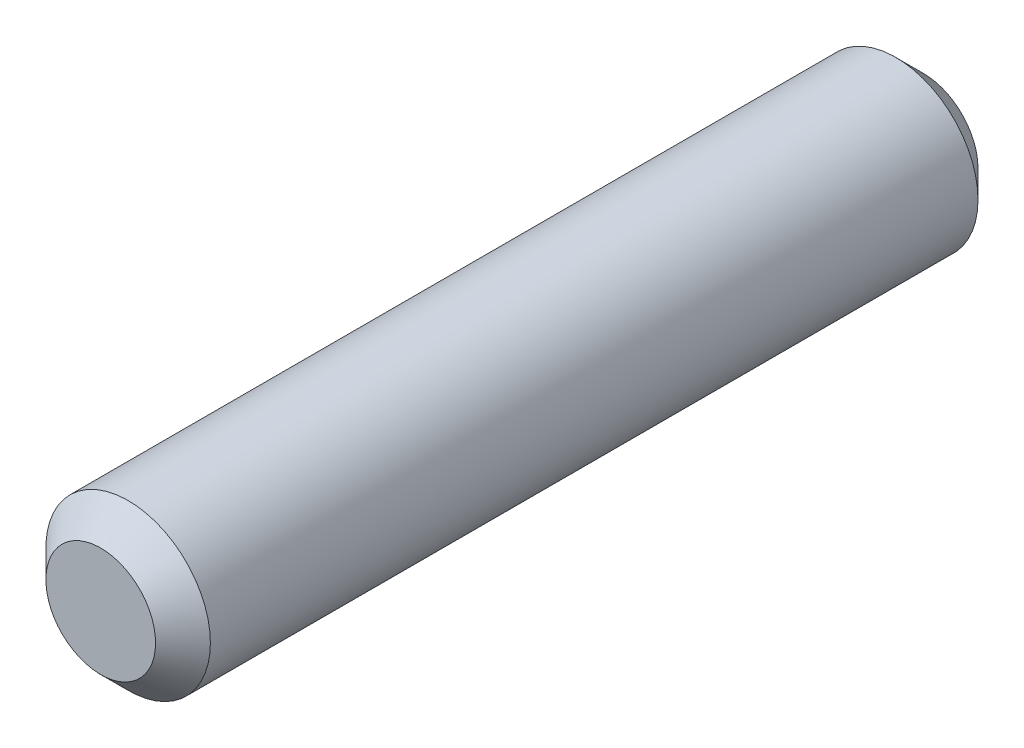
SolidWorks part; units mm, degrees
ref_plane "Спереди" through (0, 0, 0) normal (0, 0, 1) x (1, 0, 0)
ref_plane "Сверху" through (0, 0, 0) normal (0, 1, 0) x (1, 0, 0)
ref_plane "Справа" through (0, 0, 0) normal (1, 0, 0) x (0, 0, -1)
sketch "Эскиз1" plane through (0, 0, 0) normal (0, 0, 1) x (1, 0, 0)
  circle A0 centre (0, 0) radius 1.5
  point P2 (0, 0)
extrude "Бобышка-Вытянуть1" add sketch "Эскиз1" along normal blind 15
chamfer "Фаска1" distance 0.5 angle 45 2 edges at (1.5, 0, 15) (1.5, 0, 0)
